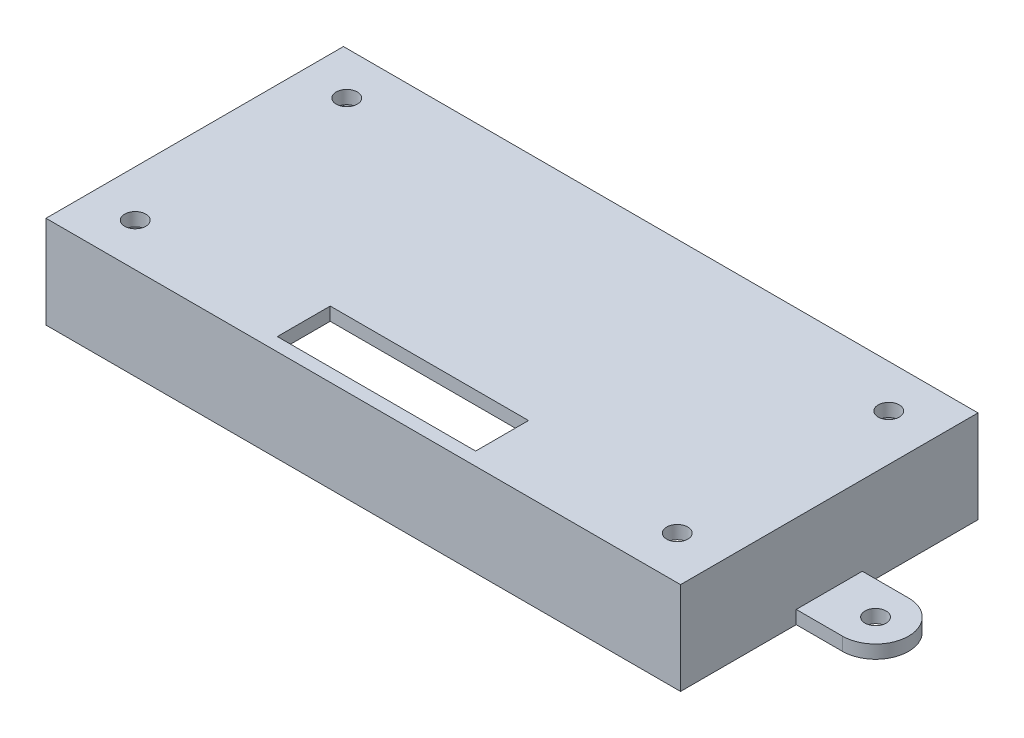
SolidWorks part; units mm, degrees
material "ABS"
ref_plane "Front Plane" through (0, 0, 0) normal (0, 0, 1) x (1, 0, 0)
ref_plane "Top Plane" through (0, 0, 0) normal (0, 1, 0) x (1, 0, 0)
ref_plane "Right Plane" through (0, 0, 0) normal (1, 0, 0) x (0, 0, -1)
sketch "Sketch1" plane through (0, 0, 0) normal (0, 1, 0) x (1, 0, 0)
  line L0 (0, 43.4315) -> (0, -42.0764) construction
  line L1 (-55, 5) -> (-48, 5)
  line L2 (-48, -22.5) -> (48, -22.5)
  line L3 (-48, -22.5) -> (-48, 22.5)
  line L4 (-48, 22.5) -> (48, 22.5)
  line L5 (48, -22.5) -> (48, 22.5)
  line L6 (-48, -22.5) -> (48, 22.5) construction
  line L7 (-48, 22.5) -> (48, -22.5) construction
  line L8 (-55, -5) -> (-48, -5)
  line L9 (55, -5) -> (48, -5)
  line L10 (55, 5) -> (48, 5)
  circle A0 centre (-55, 0) radius 5
  circle A3 centre (55, 0) radius 5
  circle A4 centre (-55, 0) radius 1.6
  circle A5 centre (55, 0) radius 1.6
  point P7 (0, 0)
  dimension "D1" = 55
  dimension "D2" = 10
  dimension "D5" = 3.2
  dimension "D3" = 96
  dimension "D4" = 45
extrude "Boss-Extrude1" add sketch "Sketch1" along normal blind 2 contours L2 L5 L4 L3 | L9 A3 L10 L5 | A3 | A0 L8 L3 L1 | A0 L5
sketch "Sketch2" plane through (0, 2, 0) normal (0, 1, 0) x (1, 0, 0)
  line L0 (-46, 20.5) -> (-46, -20.5)
  line L1 (-48, 22.5) -> (48, 22.5)
  line L2 (-48, 22.5) -> (-48, -22.5)
  line L3 (-48, -22.5) -> (48, -22.5)
  line L4 (48, 22.5) -> (48, -22.5)
  line L5 (-46, -20.5) -> (46, -20.5)
  line L6 (46, 20.5) -> (46, -20.5)
  line L7 (-46, 20.5) -> (46, 20.5)
  dimension "D1" = 2
extrude "Boss-Extrude2" add sketch "Sketch2" along normal blind 10
sketch "Sketch3" plane through (0, 2, 0) normal (0, 1, 0) x (1, 0, 0)
  line L1 (-46, -20.5) -> (46, -20.5)
  line L2 (-46, -20.5) -> (-46, 20.5)
  line L3 (-46, 20.5) -> (46, 20.5)
  line L4 (46, -20.5) -> (46, 20.5)
extrude "Cut-Extrude1" cut sketch "Sketch3" against normal through all
sketch "Sketch4" plane through (0, 12, 0) normal (0, 1, 0) x (1, 0, 0)
  line L1 (-48, 22.5) -> (48, 22.5)
  line L2 (-48, 22.5) -> (-48, -22.5)
  line L3 (-48, -22.5) -> (48, -22.5)
  line L4 (48, 22.5) -> (48, -22.5)
extrude "Boss-Extrude3" add sketch "Sketch4" along normal blind 2
sketch "Sketch5" plane through (0, 12, 0) normal (0, -1, 0) x (-1, 0, 0)
  line L1 (41, 16) -> (-41, 16)
  line L2 (41, 16) -> (41, -16)
  line L3 (41, -16) -> (-41, -16)
  line L4 (-41, 16) -> (-41, -16)
  line L5 (41, 16) -> (-41, -16) construction
  line L6 (41, -16) -> (-41, 16) construction
  circle A0 centre (41, -16) radius 1.6
  circle A1 centre (-41, -16) radius 1.6
  circle A2 centre (-41, 16) radius 1.6
  circle A3 centre (41, 16) radius 1.6
  point P0 (0, 0)
  dimension "D3" = 3.2
  dimension "D1" = 82
  dimension "D2" = 32
extrude "Cut-Extrude2" cut sketch "Sketch5" against normal through all contours L3 A0 L2 | L2 A0 L3 | L2 A3 L1 | L1 A3 L2 | L1 A2 L4 | L4 A2 L1 | L4 A1 L3 | L3 A1 L4
sketch "Sketch6" plane through (0, 12, 0) normal (0, -1, 0) x (-1, 0, 0)
  line L0 (46, -20.5) -> (-46, -20.5) construction
  line L1 (15, -20.5) -> (-15, -20.5)
  line L2 (15, -20.5) -> (15, -12.5)
  line L3 (15, -12.5) -> (-15, -12.5)
  line L4 (-15, -20.5) -> (-15, -12.5)
  point P6 (0, -12.5)
  dimension "D1" = 8
  dimension "D2" = 30
extrude "Cut-Extrude4" cut sketch "Sketch6" against normal through all
